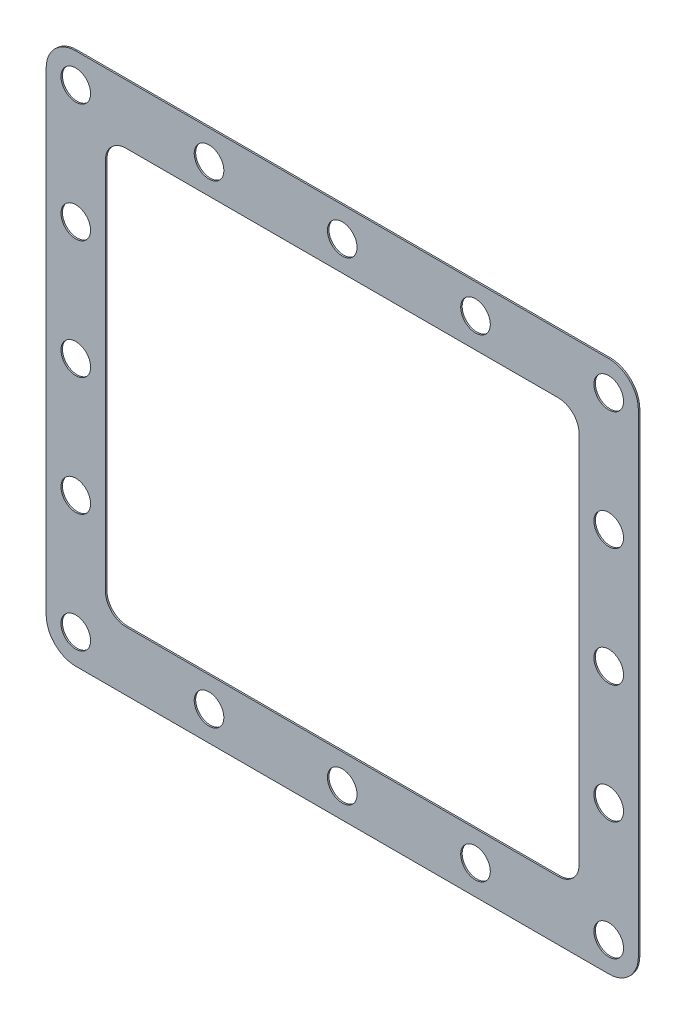
SolidWorks part; units mm, degrees
ref_plane "前视基准面" through (0, 0, 0) normal (0, 0, 1) x (1, 0, 0)
ref_plane "上视基准面" through (0, 0, 0) normal (0, 1, 0) x (1, 0, 0)
ref_plane "右视基准面" through (0, 0, 0) normal (1, 0, 0) x (0, 0, -1)
sketch "草图1" plane through (0, 0, 0) normal (0, 0, 1) x (1, 0, 0)
  line L0 (90, -80) -> (90, 80) construction
  line L1 (-90, -90) -> (90, -90)
  line L2 (-100, -80) -> (-100, 80)
  line L3 (-90, 90) -> (90, 90)
  line L4 (100, -80) -> (100, 80)
  line L5 (-100, -90) -> (100, 90) construction
  line L6 (-100, 90) -> (100, -90) construction
  line L7 (-73, -70) -> (73, -70)
  line L8 (-80, -63) -> (-80, 63)
  line L9 (-73, 70) -> (73, 70)
  line L10 (80, -63) -> (80, 63)
  line L11 (-80, -70) -> (80, 70) construction
  line L12 (-80, 70) -> (80, -70) construction
  line L13 (0, 0) -> (0, 37.6622) construction
  line L14 (0, 0) -> (41.7484, 0) construction
  line L15 (-90, 80) -> (90, 80) construction
  line L16 (-90, -80) -> (90, -80) construction
  arc A0 (90, 90) -> (100, 80) centre (90, 80) cw
  arc A1 (90, -90) -> (100, -80) centre (90, -80) ccw
  arc A2 (-90, -90) -> (-100, -80) centre (-90, -80) cw
  arc A3 (-100, 80) -> (-90, 90) centre (-90, 80) cw
  arc A4 (73, 70) -> (80, 63) centre (73, 63) cw
  arc A5 (73, -70) -> (80, -63) centre (73, -63) ccw
  arc A6 (-73, -70) -> (-80, -63) centre (-73, -63) cw
  arc A7 (-80, 63) -> (-73, 70) centre (-73, 63) cw
  circle A8 centre (90, -80) radius 5
  circle A9 centre (90, 80) radius 5
  circle A10 centre (-90, 80) radius 5
  circle A11 centre (-90, -80) radius 5
  circle A12 centre (90, 0) radius 5
  circle A13 centre (90, -40) radius 5
  circle A14 centre (90, 40) radius 5
  circle A15 centre (-90, -40) radius 5
  circle A16 centre (-90, 0) radius 5
  circle A17 centre (-90, 40) radius 5
  circle A18 centre (0, 80) radius 5
  circle A19 centre (-45, 80) radius 5
  circle A20 centre (45, 80) radius 5
  circle A21 centre (0, -80) radius 5
  circle A22 centre (-45, -80) radius 5
  circle A23 centre (45, -80) radius 5
  point P0 (0, 0)
  point P18 (0, 0)
  dimension "D3" = 10
  dimension "D6" = 7
  dimension "D7" = 10
  dimension "D8" = 10
  dimension "D9" = 10
  dimension "D10" = 10
  dimension "D11" = 10
  dimension "D12" = 10
  dimension "D13" = 10
  dimension "D14" = 40
  dimension "D15" = 40
  dimension "D16" = 10
  dimension "D17" = 10
  dimension "D18" = 10
  dimension "D19" = 45
  dimension "D20" = 45
  dimension "D21" = 10
  dimension "D22" = 10
  dimension "D23" = 45
  dimension "D24" = 45
  dimension "D25" = 10
  dimension "D1" = 180
  dimension "D2" = 200
  dimension "D4" = 20
  dimension "D5" = 20
extrude "凸台-拉伸1" add sketch "草图1" along normal blind 0.5
